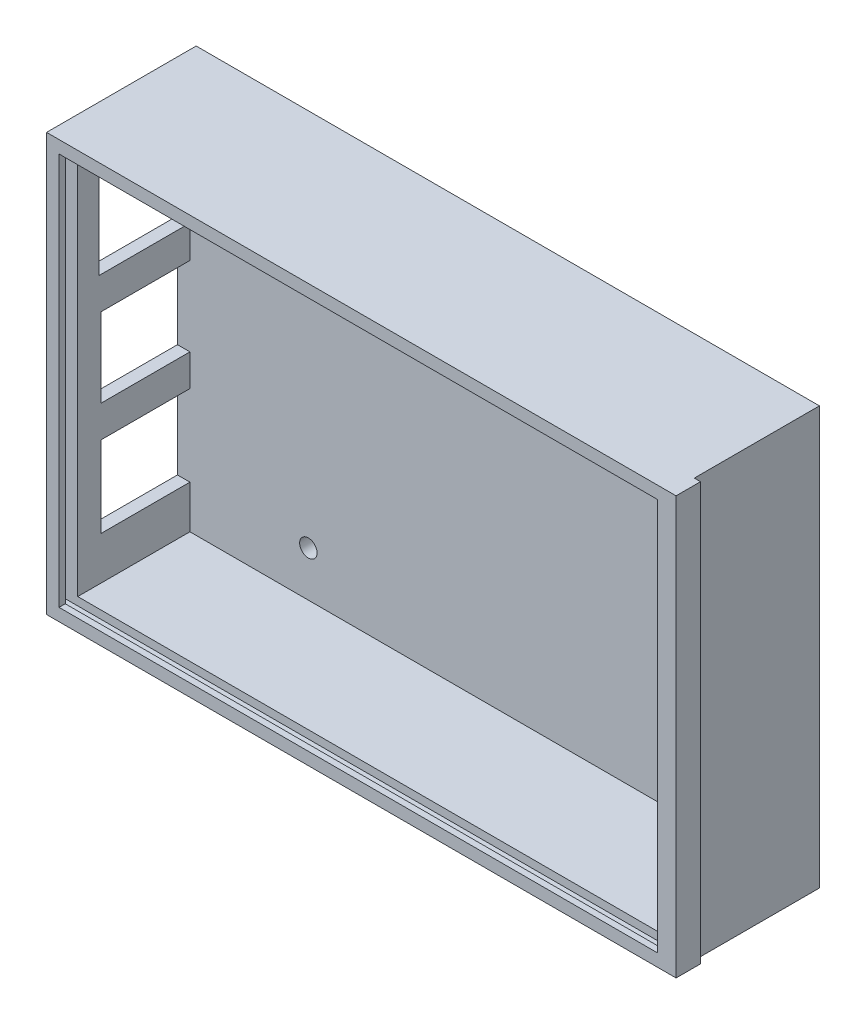
SolidWorks part; units mm, degrees
ref_plane "Front Plane" through (0, 0, 0) normal (0, 0, 1) x (1, 0, 0)
ref_plane "Top Plane" through (0, 0, 0) normal (0, 1, 0) x (1, 0, 0)
ref_plane "Right Plane" through (0, 0, 0) normal (1, 0, 0) x (0, 0, -1)
sketch "Sketch2" plane through (0, 0, 0) normal (0, 0, 1) x (1, 0, 0)
  line L1 (-50, 33.5) -> (50, 33.5)
  line L2 (-50, 33.5) -> (-50, -33.5)
  line L3 (-50, -33.5) -> (50, -33.5)
  line L4 (50, 33.5) -> (50, -33.5)
  line L5 (-50, 33.5) -> (50, -33.5) construction
  line L6 (-50, -33.5) -> (50, 33.5) construction
  point P0 (0, 0)
  dimension "D1" = 67
  dimension "D2" = 100
extrude "Boss-Extrude1" add sketch "Sketch2" along normal blind 3
sketch "Sketch3" plane through (0, 0, 3) normal (0, 0, 1) x (1, 0, 0)
  line L1 (-50, 33.5) -> (50, 33.5)
  line L2 (-50, 33.5) -> (-50, -33.5)
  line L3 (-50, -33.5) -> (50, -33.5)
  line L4 (50, 33.5) -> (50, -33.5)
  line L5 (-50, 33.5) -> (50, -33.5) construction
  line L6 (-50, -33.5) -> (50, 33.5) construction
  point P0 (0, 0)
  dimension "D1" = 100
  dimension "D2" = 67
extrude "Boss-Extrude2" add sketch "Sketch3" along normal blind 21
sketch "Sketch4" plane through (0, 0, 24) normal (0, 0, 1) x (1, 0, 0)
  line L0 (-50, -33.5) -> (50, -33.5) construction
  line L1 (-48, 31.5) -> (48, 31.5)
  line L2 (-48, 31.5) -> (-48, -31.5)
  line L3 (-48, -31.5) -> (48, -31.5)
  line L4 (48, 31.5) -> (48, -31.5)
  line L5 (-48, 31.5) -> (48, -31.5) construction
  line L6 (-48, -31.5) -> (48, 31.5) construction
  line L7 (50, -33.5) -> (50, 33.5) construction
  line L8 (50, 33.5) -> (-50, 33.5) construction
  point P0 (0, 0)
  dimension "D1" = 2
  dimension "D2" = 2
  dimension "D3" = 2
extrude "Cut-Extrude1" cut sketch "Sketch4" against normal blind 21
sketch "Sketch5" plane through (0, 0, 3) normal (0, 0, 1) x (1, 0, 0)
  line L0 (0, 0) -> (0, -33.5) construction
  line L1 (-50, -33.5) -> (50, -33.5) construction
  line L2 (0, 0) -> (0, 33.5) construction
  line L3 (50, 33.5) -> (-50, 33.5) construction
  line L4 (0, 0) -> (50, 0) construction
  line L5 (50, -33.5) -> (50, 33.5) construction
  line L6 (0, 0) -> (-50, 0) construction
  line L7 (-50, 33.5) -> (-50, -33.5) construction
  line L8 (-48, 24.25) -> (48, 24.25) construction
  line L9 (-48, 31.5) -> (-48, -31.5) construction
  line L10 (48, -31.5) -> (48, 31.5) construction
  line L11 (-48, -24.25) -> (48, -24.25) construction
  line L12 (48, -31.5) -> (48, 31.5) construction
  line L13 (0, 24.25) -> (29, 24.25) construction
  line L14 (0, 24.25) -> (-29, 24.25) construction
  line L15 (0, -24.25) -> (-29, -24.25) construction
  line L16 (0, -24.25) -> (29, -24.25) construction
  line L17 (-29, 24.25) -> (-29, -24.25) construction
  circle A0 centre (-29, 24.25) radius 1.4
  circle A1 centre (29, 24.25) radius 1.4
  circle A2 centre (29, -24.25) radius 1.4
  circle A3 centre (-29, -24.25) radius 1.4
  dimension "D5" = 2.8
  dimension "D6" = 2.8
  dimension "D7" = 2.8
  dimension "D8" = 2.8
  dimension "D1" = 29
  dimension "D2" = 29
  dimension "D3" = 29
  dimension "D4" = 29
  dimension "D10" = 24.25
  dimension "D11" = 24.25
extrude "Cut-Extrude2" cut sketch "Sketch5" against normal up to surface (3 mm away) up to face at (0, 0, 0)
sketch "Sketch9" plane through (-50, 0, 0) normal (-1, 0, 0) x (0, 0, 1)
  line L0 (3, -33.5) -> (3, 33.5) construction
  line L1 (24, -33.5) -> (0, -33.5) construction
  line L2 (24, 33.5) -> (0, 33.5) construction
  line L3 (0, 33.5) -> (0, -33.5) construction
  line L4 (3, -24.6) -> (24, -24.6) construction
  line L5 (24, 33.5) -> (24, -33.5) construction
  line L7 (3, -24.6) -> (17.3, -24.6)
  line L8 (3, -24.6) -> (3, -11.6)
  line L9 (3, -11.6) -> (17.3, -11.6)
  line L10 (17.3, -24.6) -> (17.3, -11.6)
  line L11 (3, -6.5) -> (17.3, -6.5)
  line L12 (3, -6.5) -> (3, 6.2)
  line L13 (3, 6.2) -> (17.3, 6.2)
  line L14 (17.3, -6.5) -> (17.3, 6.2)
  line L15 (3, 11.4) -> (17.6, 11.4)
  line L16 (3, 11.4) -> (3, 26.7)
  line L17 (3, 26.7) -> (17.6, 26.7)
  line L18 (17.6, 11.4) -> (17.6, 26.7)
  dimension "D1" = 3
  dimension "D2" = 8.9
  dimension "D3" = 13
  dimension "D4" = 14.3
  dimension "D5" = 5.1
  dimension "D6" = 14.3
  dimension "D7" = 12.7
  dimension "D8" = 5.2
  dimension "D9" = 15.3
  dimension "D10" = 14.6
extrude "Cut-Extrude5" cut sketch "Sketch9" against normal up to surface (2 mm away) up to face at (-48, 0, 13.5)
sketch "Sketch12" plane through (50, 0, 0) normal (1, 0, 0) x (0, 0, -1)
  line L0 (-23, 33.5) -> (-23, -33.5) construction
  line L1 (-24, 33.5) -> (0, 33.5) construction
  line L2 (-24, -33.5) -> (0, -33.5) construction
  line L3 (-24, -33.5) -> (-24, 33.5) construction
  line L5 (-23, 32.8) -> (-21, 32.8)
  line L6 (-23, 32.8) -> (-23, -32.8)
  line L7 (-23, -32.8) -> (-21, -32.8)
  line L8 (-21, 32.8) -> (-21, -32.8)
  point P12 (-22, -32.8)
  dimension "D1" = 1
  dimension "D2" = 2
  dimension "D3" = 0.7
  dimension "D4" = 0.7
extrude "Cut-Extrude7" cut sketch "Sketch12" against normal up to surface (100 mm away)
sketch "Sketch16" plane through (50, 0, 0) normal (1, 0, 0) x (0, 0, -1)
  line L0 (-24, -33.5) -> (0, -33.5) construction
  line L1 (-24, 33.5) -> (-20.0797, 33.5)
  line L2 (-24, 33.5) -> (-24, -33.5)
  line L3 (-24, -33.5) -> (-20.0797, -33.5)
  line L4 (-20.0797, 33.5) -> (-20.0797, -33.5)
extrude "Boss-Extrude3" add sketch "Sketch16" along normal blind 1
